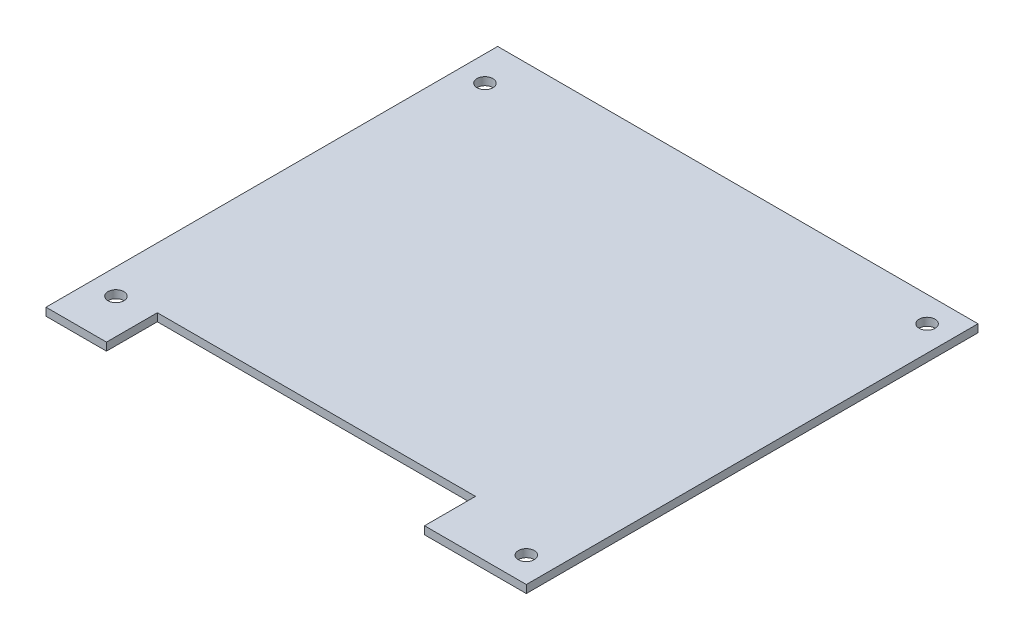
SolidWorks part; units mm, degrees
material "E-Glass Fiber"
ref_plane "Front Plane" through (0, 0, 0) normal (0, 0, 1) x (1, 0, 0)
ref_plane "Top Plane" through (0, 0, 0) normal (0, 1, 0) x (1, 0, 0)
ref_plane "Right Plane" through (0, 0, 0) normal (1, 0, 0) x (0, 0, -1)
sketch "Sketch1" plane through (0, 0, 0) normal (0, 1, 0) x (1, 0, 0)
  line L0 (-35.875, -45.085) -> (-47.945, -45.085)
  line L1 (47.945, -45.085) -> (27.625, -45.085)
  line L2 (47.945, -45.085) -> (47.945, 45.085)
  line L3 (47.945, 45.085) -> (-47.945, 45.085)
  line L4 (-47.945, -45.085) -> (-47.945, 45.085)
  line L5 (47.945, -45.085) -> (-47.945, 45.085) construction
  line L6 (47.945, 45.085) -> (-47.945, -45.085) construction
  line L8 (-35.875, -45.085) -> (-35.875, -34.925)
  line L9 (-35.875, -34.925) -> (27.625, -34.925)
  line L10 (27.625, -45.085) -> (27.625, -34.925)
  point P0 (0, 0)
  dimension "D1" = 90.17
  dimension "D2" = 95.89
  dimension "D3" = 20.32
  dimension "D4" = 10.16
  dimension "D5" = 83.82
extrude "Boss-Extrude1" add sketch "Sketch1" along normal blind 1.57
sketch "Sketch2" plane through (0, 1.57, 0) normal (0, 1, 0) x (1, 0, 0)
  line L0 (27.625, -45.085) -> (47.945, -45.085) construction
  line L1 (47.945, -45.085) -> (47.945, 45.085) construction
  circle A0 centre (42.865, -40.005) radius 1.59
  circle A1 centre (-42.865, -36.195) radius 1.59
  circle A2 centre (-42.865, 37.465) radius 1.59
  circle A3 centre (42.865, 40.005) radius 1.59
  dimension "D3" = 3.18
  dimension "D6" = 3.18
  dimension "D9" = 3.18
  dimension "D12" = 3.18
  dimension "D1" = 5.08
  dimension "D2" = 5.08
  dimension "D4" = 8.89
  dimension "D5" = 90.81
  dimension "D7" = 5.08
  dimension "D8" = 85.09
  dimension "D10" = 90.81
  dimension "D11" = 82.55
extrude "Cut-Extrude1" cut sketch "Sketch2" against normal through all
